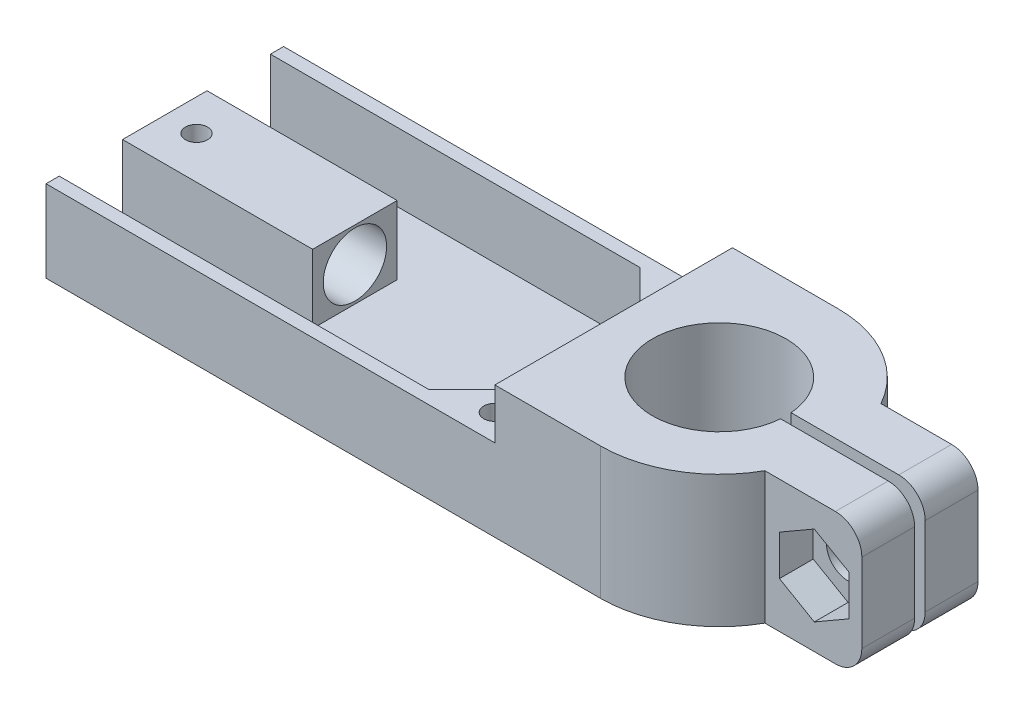
SolidWorks part; units mm, degrees
ref_plane "Front Plane" through (0, 0, 0) normal (0, 0, 1) x (1, 0, 0)
ref_plane "Top Plane" through (0, 0, 0) normal (0, 1, 0) x (1, 0, 0)
ref_plane "Right Plane" through (0, 0, 0) normal (1, 0, 0) x (0, 0, -1)
sketch "Sketch1" plane through (0, 0, 0) normal (0, 1, 0) x (1, 0, 0)
  line L0 (0, -22.5) -> (-105, -22.5)
  line L1 (-105, -22.5) -> (-105, 22.5)
  line L2 (-105, 22.5) -> (0, 22.5)
  line L4 (22, -1) -> (12.6104, -1)
  line L5 (19.6278, -11) -> (38, -11)
  line L7 (22, -1) -> (38, -1)
  line L8 (38, -11) -> (38, -1)
  line L9 (19.6278, 11) -> (38, 11)
  line L11 (22, 1) -> (38, 1)
  line L12 (38, 11) -> (38, 1)
  line L13 (22, 1) -> (12.6104, 1)
  line L14 (0, 0) -> (50.2847, 0) construction
  line L15 (38, 1) -> (38, -1) construction
  arc A0 (12.6104, 1) -> (12.6104, -1) centre (0, 0) ccw
  arc A1 (0, -22.5) -> (19.6278, -11) centre (0, 0) ccw
  arc A2 (19.6278, 11) -> (0, 22.5) centre (0, 0) ccw
  point P15 (38, 0)
  dimension "D1" = 25.3
  dimension "D2" = 45
  dimension "D3" = 105
  dimension "D5" = 38
  dimension "D6" = 38
  dimension "D4" = 2
  dimension "D7" = 10
extrude "Boss-Extrude1" add sketch "Sketch1" along normal blind 25
sketch "Sketch2" plane through (-105, 0, 0) normal (-1, 0, 0) x (0, 0, 1)
  line L0 (-22.5, 25) -> (22.5, 25) construction
  line L1 (-20, 25) -> (20, 25)
  line L2 (-20, 15.5) -> (-20, 2.5)
  line L3 (-20, 2.5) -> (20, 2.5)
  line L4 (20, 15.5) -> (20, 2.5)
  line L5 (22.5, 25) -> (22.5, 0) construction
  line L6 (-22.5, 0) -> (22.5, 0) construction
  line L7 (-22.5, 25) -> (-22.5, 0) construction
  line L8 (-20, 15.5) -> (-22.5, 15.5)
  line L9 (22.5, 25) -> (-22.5, 25)
  line L10 (22.5, 25) -> (22.5, 15.5)
  line L11 (22.5, 15.5) -> (20, 15.5)
  line L12 (-22.5, 25) -> (-22.5, 15.5)
  line M6 (22.5, 0) -> (22.5, 25)
  line M7 (22.5, 25) -> (-22.5, 25)
  line M8 (-22.5, 25) -> (-22.5, 0)
  dimension "D1" = 2.5
  dimension "D2" = 2.5
  dimension "D3" = 2.5
  dimension "D4" = 15.5
extrude "Cut-Extrude1" cut sketch "Sketch2" against normal blind 85 contours L11 L8 L2 L3 L4 M6 M7 M8
sketch "Sketch3" plane through (0, 2.5, 0) normal (0, 1, 0) x (1, 0, 0)
  line L0 (-105, 20) -> (-105, -20) construction
  line L1 (-105, -8) -> (-69, -8)
  line L2 (-105, -8) -> (-105, 8)
  line L3 (-105, 8) -> (-69, 8)
  line L4 (-69, -8) -> (-69, 8)
  line L5 (-20, -20) -> (-105, -20) construction
  line L6 (-20, 20) -> (-105, 20) construction
  line M5 (-105, 20) -> (-105, -20)
  dimension "D1" = 12
  dimension "D2" = 12
  dimension "D3" = 36
extrude "Boss-Extrude2" add sketch "Sketch3" along normal up to vertex (13 mm away) contours L1 L4 L3 M5 up to point (-105, 15.5, 20)
sketch "Sketch4" plane through (-69, 0, 0) normal (1, 0, 0) x (0, 0, -1)
  line L0 (8, 2.5) -> (-8, 15.5) construction
  line L1 (-8, 15.5) -> (8, 15.5) construction
  line L2 (-8, 15.5) -> (-8, 2.5) construction
  circle A0 centre (0, 9) radius 6
  dimension "D1" = 12
extrude "Cut-Extrude2" cut sketch "Sketch4" against normal blind 23
sketch "Sketch6" plane through (0, 2.5, 0) normal (0, 1, 0) x (1, 0, 0)
  line L0 (-35, -20) -> (-20, -5)
  line L1 (-20, -20) -> (-105, -20) construction
  line L2 (-20, 20) -> (-20, -20) construction
  line L3 (-20, -5) -> (-20, -20)
  line L4 (-20, -20) -> (-35, -20)
  line L5 (-20, 20) -> (-20, 5)
  line L6 (-20, 5) -> (-35, 20)
  line L7 (-20, 20) -> (-105, 20) construction
  line L8 (-35, 20) -> (-20, 20)
  dimension "D1" = 15
  dimension "D2" = 15
  dimension "D3" = 15
  dimension "D4" = 15
extrude "Boss-Extrude3" add sketch "Sketch6" along normal up to vertex (13 mm away) up to point (-20, 15.5, 20)
sketch "Sketch7" plane through (0, 15.5, 0) normal (0, 1, 0) x (1, 0, 0)
  line L0 (-20, -22.5) -> (-20, -5) construction
  line L1 (-20, -22.5) -> (-105, -22.5) construction
  line L2 (-20, 22.5) -> (-105, 22.5) construction
  line L3 (-20, 5) -> (-20, 22.5) construction
  line L4 (-105, 8) -> (-105, -8) construction
  circle A0 centre (-25, -17.5) radius 2.1
  circle A1 centre (-25, 17.5) radius 2.1
  circle A2 centre (-99, 0) radius 2.1
  dimension "D6" = 4.2
  dimension "D7" = 4.2
  dimension "D8" = 4.2
  dimension "D1" = 5
  dimension "D2" = 5
  dimension "D3" = 5
  dimension "D4" = 5
  dimension "D5" = 6
extrude "Cut-Extrude4" cut sketch "Sketch7" against normal up to next
sketch "Sketch8" plane through (0, 0, 0) normal (0, -1, 0) x (-1, 0, 0)
  line L0 (105, 22.5) -> (105, -22.5) construction
  line L1 (20.8431, 17.5) -> (22.9215, 13.9)
  line L2 (22.9215, 13.9) -> (27.0785, 13.9)
  line L3 (27.0785, 13.9) -> (29.1569, 17.5)
  line L4 (29.1569, 17.5) -> (27.0785, 21.1)
  line L5 (27.0785, 21.1) -> (22.9215, 21.1)
  line L6 (22.9215, 21.1) -> (20.8431, 17.5)
  line L7 (20.8431, -17.5) -> (22.9215, -21.1)
  line L8 (22.9215, -21.1) -> (27.0785, -21.1)
  line L9 (27.0785, -21.1) -> (29.1569, -17.5)
  line L10 (29.1569, -17.5) -> (27.0785, -13.9)
  line L11 (27.0785, -13.9) -> (22.9215, -13.9)
  line L12 (22.9215, -13.9) -> (20.8431, -17.5)
  line L13 (99, -4.1569) -> (102.6, -2.0785)
  line L14 (102.6, -2.0785) -> (102.6, 2.0785)
  line L15 (102.6, 2.0785) -> (99, 4.1569)
  line L16 (99, 4.1569) -> (95.4, 2.0785)
  line L17 (95.4, 2.0785) -> (95.4, -2.0785)
  line L18 (95.4, -2.0785) -> (99, -4.1569)
  circle A0 centre (25, 17.5) radius 3.6 construction
  circle A1 centre (25, -17.5) radius 3.6 construction
  circle A2 centre (99, 0) radius 3.6 construction
  point P29 (21.8823, 15.7)
  dimension "D1" = 7.2
  dimension "D2" = 7.2
  dimension "D3" = 7.2
extrude "Cut-Extrude5" cut sketch "Sketch8" against normal offset from surface (11.5 mm away) 4 up to face at (-25, 15.5, 19.6)
sketch "Sketch10" plane through (0, 0, 11) normal (0, 0, 1) x (1, 0, 0)
  line L0 (29, 25) -> (29, 0) construction
  line L1 (19.6278, 25) -> (38, 25) construction
  line L2 (19.6278, 0) -> (38, 0) construction
  line L3 (38, 25) -> (38, 0) construction
  circle A0 centre (29, 12.5) radius 4.1
  point P9 (29, 12.5)
  dimension "D1" = 8.2
  dimension "D2" = 9
extrude "Cut-Extrude6" cut sketch "Sketch10" against normal through all
sketch "Sketch11" plane through (0, 0, 11) normal (0, 0, -1) x (-1, 0, 0)
  line L1 (-35.6, 16.3105) -> (-35.6, 8.6895)
  line L2 (-35.6, 8.6895) -> (-29, 4.879)
  line L3 (-29, 4.879) -> (-22.4, 8.6895)
  line L4 (-22.4, 8.6895) -> (-22.4, 16.3105)
  line L5 (-22.4, 16.3105) -> (-29, 20.121)
  line L6 (-29, 20.121) -> (-35.6, 16.3105)
  circle A0 centre (-29, 12.5) radius 4.1 construction
  circle A1 centre (-29, 12.5) radius 4.1
  circle A2 centre (-29, 12.5) radius 6.6 construction
  dimension "D1" = 13.2
extrude "Cut-Extrude7" cut sketch "Sketch11" along normal blind 6.4
fillet "Fillet1" radius 5 4 edges at (38, 0, 6) (38, 0, -6) (38, 25, -6) (38, 25, 6)
equation "\"D5@Sketch1\"=\"D6@Sketch1\""
